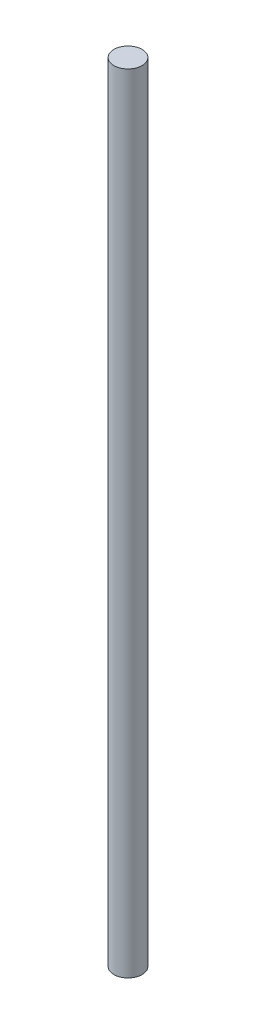
SolidWorks part; units mm, degrees
ref_plane "Front Plane" through (0, 0, 0) normal (0, 0, 1) x (1, 0, 0)
ref_plane "Top Plane" through (0, 0, 0) normal (0, 1, 0) x (1, 0, 0)
ref_plane "Right Plane" through (0, 0, 0) normal (1, 0, 0) x (0, 0, -1)
sketch "Sketch1" plane through (0, 0, 0) normal (0, 1, 0) x (1, 0, 0)
  circle A0 centre (0, 0) radius 5
extrude "Boss-Extrude1" add sketch "Sketch1" along normal blind 280
